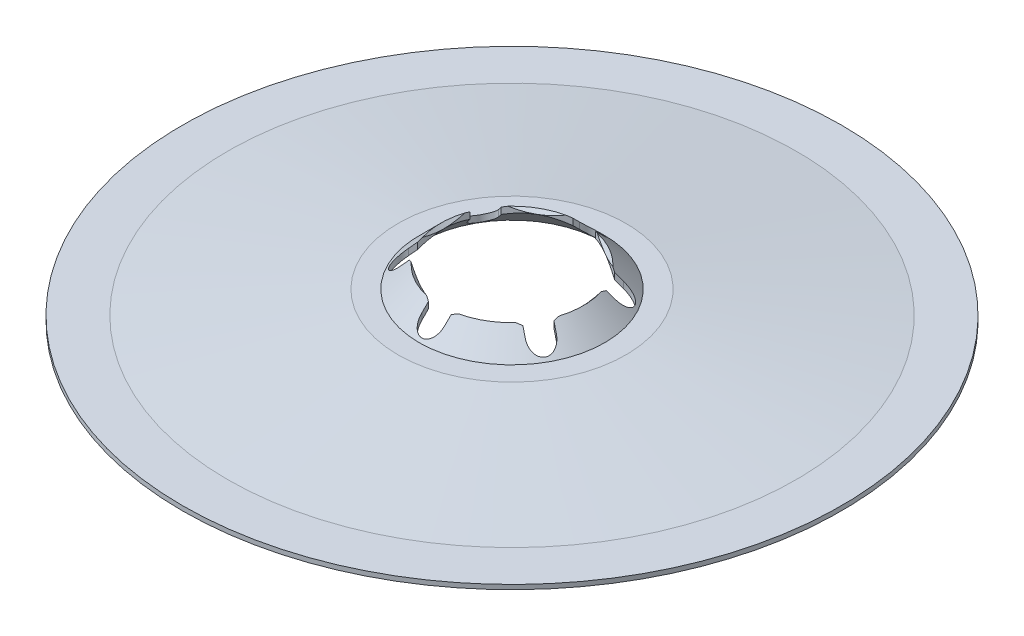
SolidWorks part; units mm, degrees
ref_plane "Front Plane" through (0, 0, 0) normal (0, 0, 1) x (1, 0, 0)
ref_plane "Top Plane" through (0, 0, 0) normal (0, 1, 0) x (1, 0, 0)
ref_plane "Right Plane" through (0, 0, 0) normal (1, 0, 0) x (0, 0, -1)
sketch "Sketch1" plane through (0, 0, 0) normal (1, 0, 0) x (0, 0, -1)
  line L6 (0, 0) -> (0, 0.2)
  line L7 (0, 0.2) -> (1.9867, 0.2)
  line L8 (1.9867, 0.2) -> (9.4867, 1.2)
  line L9 (9.4867, 1.2) -> (14.5, 1.2) construction
  line L10 (14.5, 1.2) -> (14.5, 1) construction
  line L11 (14.5, 1) -> (9.5, 1) construction
  line L12 (9.5, 1) -> (2, 0)
  line L13 (2, 0) -> (0, 0)
  line L14 (2, 0) -> (1.9736, 0.1982) construction
  line L15 (9.4867, 1.2) -> (10.4172, 1.2)
  line L16 (10.4172, 1.2) -> (11.3586, 2.1414)
  line L17 (11.3586, 2.1414) -> (11.5, 2)
  line L18 (11.5, 2) -> (10.5, 1)
  line L19 (10.5, 1) -> (9.5, 1)
  point P12 (11.3719, 2.1536)
  dimension "D1" = 14.5
  dimension "D2" = 0.2
  dimension "D3" = 5
  dimension "D4" = 1
  dimension "D5" = 2
  dimension "D6" = 3
  dimension "D7" = 1
  dimension "D8" = 1
revolve "Revolve1" add sketch "Sketch1" angle 360 about L10
sketch "Sketch3" plane through (0, 0, 0) normal (0, 1, 0) x (1, 0, 0)
  line L0 (3, 12.7679) -> (1.7321, 13.5) construction
  line L1 (3, 12.7679) -> (3, 16.2321) construction
  line L2 (3, 16.2321) -> (0, 17.9641) construction
  line L3 (0, 17.9641) -> (-3, 16.2321) construction
  line L4 (-3, 16.2321) -> (-3, 12.7679) construction
  line L5 (-3, 12.7679) -> (0, 11.0359) construction
  line L6 (0, 11.0359) -> (3, 12.7679) construction
  line L7 (2.3094, 14.5) -> (1.1547, 16.5) construction
  line L8 (1.1547, 16.5) -> (-1.1547, 16.5) construction
  line L9 (-1.1547, 16.5) -> (-2.3094, 14.5) construction
  line L10 (-2.3094, 14.5) -> (-1.1547, 12.5) construction
  line L11 (-1.1547, 12.5) -> (1.1547, 12.5) construction
  line L12 (1.1547, 12.5) -> (2.3094, 14.5) construction
  line L13 (3.25, 13.201) -> (1.9821, 13.933) construction
  line L14 (2.75, 12.3349) -> (1.4821, 13.067) construction
  line L15 (3.25, 13.201) -> (3, 13.3453)
  line L16 (2.75, 12.3349) -> (2.5, 12.4793)
  line L17 (-0.5, 11.0359) -> (-0.5, 11.3246)
  line L18 (0.5, 11.0359) -> (0.5, 11.3246)
  line L19 (-3.25, 13.201) -> (-3, 13.3453)
  line L20 (-2.75, 12.3349) -> (-2.5, 12.4793)
  line L21 (-2.75, 16.6651) -> (-2.5, 16.5207)
  line L22 (-3.25, 15.799) -> (-3, 15.6547)
  line L23 (0.5, 17.9641) -> (0.5, 17.6754)
  line L24 (-0.5, 17.9641) -> (-0.5, 17.6754)
  line L25 (3.25, 15.799) -> (3, 15.6547)
  line L26 (2.75, 16.6651) -> (2.5, 16.5207)
  line L27 (2.5, 12.4793) -> (0.5, 11.3246)
  line L28 (-0.5, 11.3246) -> (-2.5, 12.4793)
  line L29 (-3, 13.3453) -> (-3, 15.6547)
  line L30 (-2.5, 16.5207) -> (-0.5, 17.6754)
  line L31 (0.5, 17.6754) -> (2.5, 16.5207)
  line L32 (3, 15.6547) -> (3, 13.3453)
  circle A0 centre (0, 14.5) radius 3 construction
  circle A1 centre (0, 14.5) radius 2 construction
  arc A3 (2.75, 12.3349) -> (3.25, 13.201) centre (3, 12.7679) ccw
  arc A8 (-0.5, 11.0359) -> (0.5, 11.0359) centre (0, 11.0359) ccw
  arc A9 (-3.25, 13.201) -> (-2.75, 12.3349) centre (-3, 12.7679) ccw
  arc A10 (-2.75, 16.6651) -> (-3.25, 15.799) centre (-3, 16.2321) ccw
  arc A11 (0.5, 17.9641) -> (-0.5, 17.9641) centre (0, 17.9641) ccw
  arc A12 (3.25, 15.799) -> (2.75, 16.6651) centre (3, 16.2321) ccw
  point P1 (0, 0)
  point P50 (0, 14.5)
  point P61 (0, 14.5)
  dimension "D2" = 0.5
  dimension "D1" = 6
  dimension "D3" = 4
  dimension "D4" = 6
  dimension "D5" = 6
extrude "Cut-Extrude2" cut sketch "Sketch3" along normal blind 10
